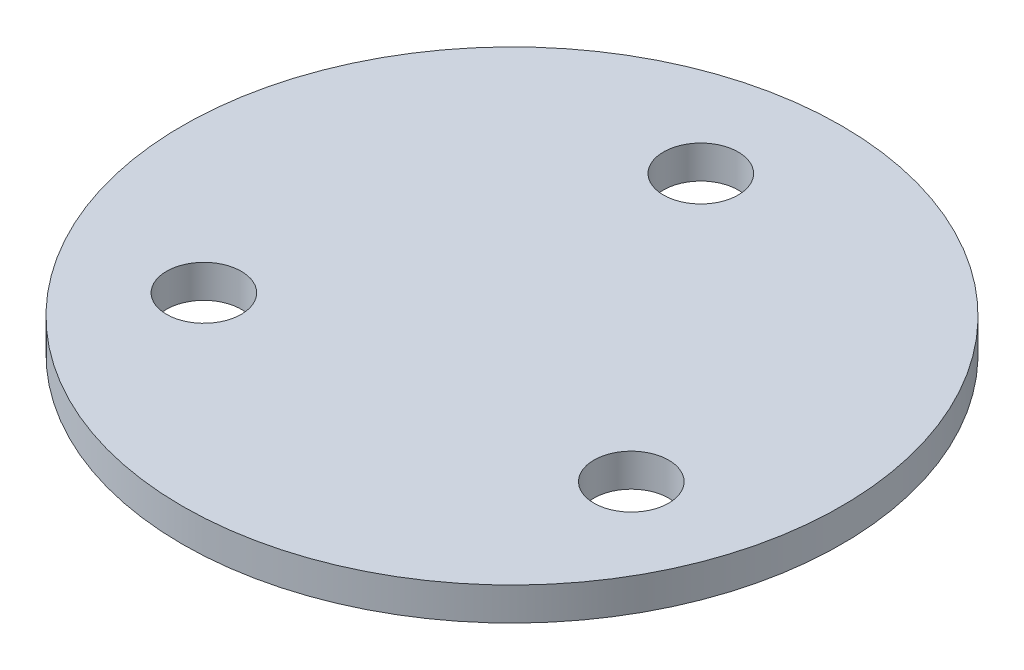
SolidWorks part; units mm, degrees
ref_plane "Front Plane" through (0, 0, 0) normal (0, 0, 1) x (1, 0, 0)
ref_plane "Top Plane" through (0, 0, 0) normal (0, 1, 0) x (1, 0, 0)
ref_plane "Right Plane" through (0, 0, 0) normal (1, 0, 0) x (0, 0, -1)
sketch "Sketch1" plane through (0, 0, 0) normal (0, 1, 0) x (1, 0, 0)
  circle A0 centre (0, 0) radius 15
  circle A1 centre (9.244, -3.8143) radius 1.7
  circle A2 centre (-7.9253, -6.0984) radius 1.7
  circle A3 centre (-1.3187, 9.9127) radius 1.7
extrude "Boss-Extrude1" add sketch "Sketch1" along normal blind 1.5
